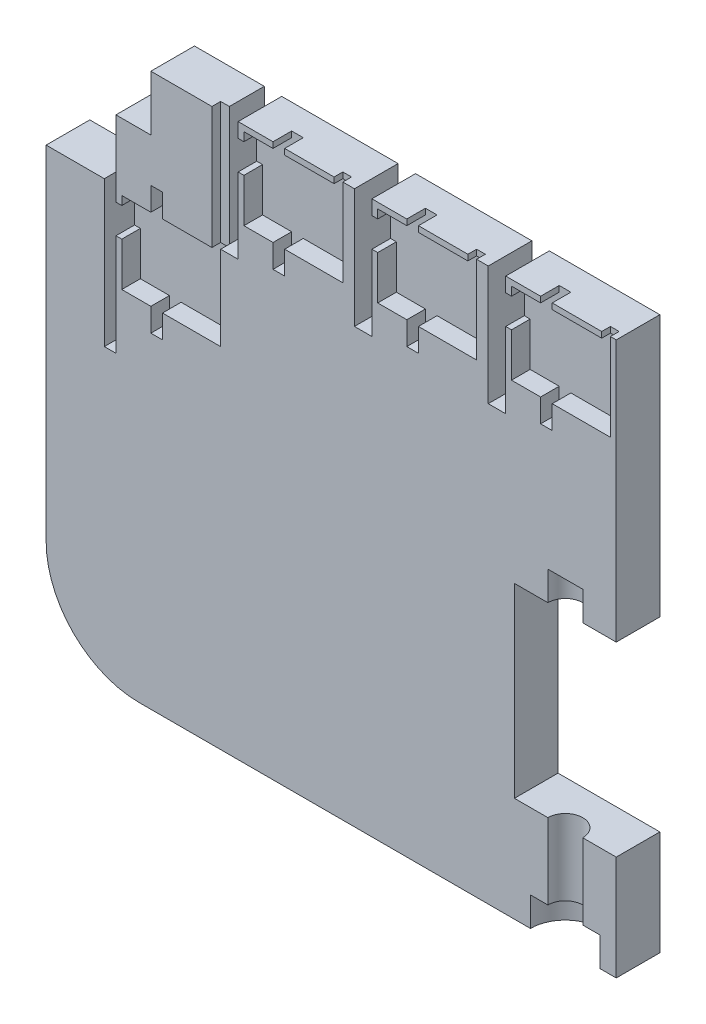
SolidWorks part; units mm, degrees
ref_plane "Front Plane" through (0, 0, 0) normal (0, 0, 1) x (1, 0, 0)
ref_plane "Top Plane" through (0, 0, 0) normal (0, 1, 0) x (1, 0, 0)
ref_plane "Right Plane" through (0, 0, 0) normal (1, 0, 0) x (0, 0, -1)
sketch "Sketch1" plane through (0, 0, 0) normal (0, 0, 1) x (1, 0, 0)
  line L1 (-33, -47.5) -> (49, -47.5)
  line L2 (-49, -31.5) -> (-49, 47.5)
  line L3 (-49, 47.5) -> (27, 47.5)
  line L4 (49, -47.5) -> (49, -29.5)
  line L5 (-49, -47.5) -> (49, 47.5) construction
  line L6 (-49, 47.5) -> (49, -47.5) construction
  line L10 (49, 2.5) -> (31.5, 2.5)
  line L11 (31.5, 2.5) -> (31.5, -29.5)
  line L12 (31.5, -29.5) -> (49, -29.5)
  line L13 (49, 2.5) -> (49, 47.5)
  line L14 (30, 47.5) -> (49, 47.5)
  line L16 (30, 47.5) -> (30, 30.5)
  line L17 (30, 30.5) -> (27, 30.5)
  line L18 (27, 47.5) -> (27, 30.5)
  arc A0 (-33, -47.5) -> (-49, -31.5) centre (-33, -31.5) cw
  point P0 (0, 0)
  point P15 (30, 39)
  dimension "D3" = 16
  dimension "D1" = 98
  dimension "D2" = 95
  dimension "D4" = 18
  dimension "D5" = 17.5
  dimension "D6" = 32
  dimension "D7" = 17
  dimension "D8" = 19
  dimension "D9" = 3
extrude "Boss-Extrude1" add sketch "Sketch1" along normal blind 7.5
sketch "Sketch2" plane through (0, 0, 7.5) normal (0, 0, 1) x (1, 0, 0)
  line L0 (30, 40) -> (31, 40)
  line L1 (30, 47.5) -> (30, 30.5) construction
  line L2 (31, 40) -> (31, 32.5)
  line L3 (31, 32.5) -> (36, 32.5)
  line L4 (36, 32.5) -> (36, 28.5)
  line L5 (36, 28.5) -> (38, 28.5)
  line L6 (38, 28.5) -> (38, 32.5)
  line L7 (38, 32.5) -> (48, 32.5)
  line L8 (48, 32.5) -> (48, 46.5)
  line L9 (48, 46.5) -> (38, 46.5)
  line L10 (31, 46.5) -> (31, 45)
  line L11 (31, 45) -> (30, 45)
  line L12 (30, 45) -> (30, 40)
  line L13 (-16, 40) -> (-15, 40)
  line L14 (36, 46.5) -> (36, 47.5)
  line L15 (49, 47.5) -> (30, 47.5) construction
  line L16 (36, 47.5) -> (38, 47.5)
  line L17 (38, 47.5) -> (38, 46.5)
  line L19 (36, 46.5) -> (31, 46.5)
  line L20 (7, 40) -> (8, 40)
  line L21 (8, 40) -> (8, 32.5)
  line L22 (8, 32.5) -> (13, 32.5)
  line L23 (13, 32.5) -> (13, 28.5)
  line L24 (13, 28.5) -> (15, 28.5)
  line L25 (15, 28.5) -> (15, 32.5)
  line L26 (15, 32.5) -> (25, 32.5)
  line L27 (25, 32.5) -> (25, 46.5)
  line L28 (25, 46.5) -> (15, 46.5)
  line L29 (8, 46.5) -> (8, 45)
  line L30 (8, 45) -> (7, 45)
  line L31 (7, 45) -> (7, 40)
  line L32 (13, 46.5) -> (13, 47.5)
  line L33 (13, 47.5) -> (15, 47.5)
  line L34 (15, 47.5) -> (15, 46.5)
  line L35 (13, 46.5) -> (8, 46.5)
  line L36 (49, 2.5) -> (49, 47.5) construction
  line L37 (27, 47.5) -> (-49, 47.5) construction
  line L38 (-15, 40) -> (-15, 32.5)
  line L39 (-15, 32.5) -> (-10, 32.5)
  line L40 (-10, 32.5) -> (-10, 28.5)
  line L41 (-10, 28.5) -> (-8, 28.5)
  line L42 (-8, 28.5) -> (-8, 32.5)
  line L43 (-8, 32.5) -> (2, 32.5)
  line L44 (2, 32.5) -> (2, 46.5)
  line L45 (2, 46.5) -> (-8, 46.5)
  line L46 (-15, 46.5) -> (-15, 45)
  line L47 (-15, 45) -> (-16, 45)
  line L48 (-16, 45) -> (-16, 40)
  line L49 (-10, 46.5) -> (-10, 47.5)
  line L50 (-10, 47.5) -> (-8, 47.5)
  line L51 (-8, 47.5) -> (-8, 46.5)
  line L52 (-10, 46.5) -> (-15, 46.5)
  point P4 (30, 42.5)
  dimension "D1" = 1
  dimension "D2" = 5
  dimension "D3" = 5
  dimension "D4" = 4
  dimension "D5" = 17
  dimension "D6" = 10
  dimension "D7" = 2
  dimension "D8" = 4
  dimension "D9" = 14
  dimension "D10" = 24
  dimension "D11" = 1
  dimension "D12" = 6
extrude "Cut-Extrude1" cut sketch "Sketch2" against normal blind 3.2
sketch "Sketch3" plane through (0, -47.5, 0) normal (0, -1, 0) x (1, 0, 0)
  line L0 (-33, 7.5) -> (49, 7.5) construction
  line L2 (49, 7.5) -> (31.5, 7.5) construction
  line L4 (34.25, 7.5) -> (46.25, 7.5)
  arc A0 (46.25, 7.5) -> (34.25, 7.5) centre (40.25, 7.5) cw
  point P6 (40.25, 7.5)
  dimension "D2" = 6
  dimension "D1" = 17.5
extrude "Cut-Extrude2" cut sketch "Sketch3" against normal blind 5
sketch "Sketch4" plane through (0, -42.5, 0) normal (0, -1, 0) x (1, 0, 0)
  line L0 (46.25, 7.5) -> (34.25, 7.5) construction
  line L1 (37.25, 7.5) -> (43.25, 7.5)
  arc A0 (43.25, 7.5) -> (37.25, 7.5) centre (40.25, 7.5) cw
  dimension "D1" = 3
extrude "Cut-Extrude3" cut sketch "Sketch4" against normal blind 50
sketch "Sketch5" plane through (0, 0, 7.5) normal (0, 0, 1) x (1, 0, 0)
  line L0 (7, 47.5) -> (7, 30.5)
  line L1 (13, 47.5) -> (-8, 47.5) construction
  line L2 (7, 30.5) -> (4, 30.5)
  line L3 (4, 30.5) -> (4, 47.5)
  line L4 (4, 47.5) -> (7, 47.5)
  line L5 (27, 30.5) -> (27, 47.5) construction
  line L6 (30, 30.5) -> (27, 30.5) construction
  line L7 (7, 45) -> (7, 40) construction
  line L8 (-16, 47.5) -> (-16, 30.5)
  line L9 (-10, 47.5) -> (-49, 47.5) construction
  line L10 (-16, 30.5) -> (-19, 30.5)
  line L11 (-19, 30.5) -> (-19, 47.5)
  line L12 (-19, 47.5) -> (-16, 47.5)
  line L13 (-16, 45) -> (-16, 40) construction
extrude "Cut-Extrude4" cut sketch "Sketch5" against normal up to next
sketch "Sketch8" plane through (0, 0, 7.5) normal (0, 0, 1) x (1, 0, 0)
  line L0 (-19, 47.5) -> (-49, 47.5) construction
  line L1 (-37, 47.5) -> (-49, 47.5)
  line L2 (-37, 47.5) -> (-37, 10.5)
  line L3 (-37, 10.5) -> (-49, 10.5)
  line L4 (-49, 47.5) -> (-49, 10.5)
  line L5 (-49, 47.5) -> (-49, -31.5) construction
  dimension "D1" = 12
  dimension "D2" = 37
extrude "Cut-Extrude5" cut sketch "Sketch8" against normal up to next
sketch "Sketch9" plane through (0, 0, 7.5) normal (0, 0, 1) x (1, 0, 0)
  line L0 (-37, 20) -> (-36, 20)
  line L1 (-36, 20) -> (-36, 12.5)
  line L2 (-36, 12.5) -> (-31, 12.5)
  line L3 (-31, 12.5) -> (-31, 8.5)
  line L4 (-31, 8.5) -> (-29, 8.5)
  line L5 (-29, 8.5) -> (-29, 12.5)
  line L6 (-29, 12.5) -> (-19, 12.5)
  line L7 (-19, 12.5) -> (-19, 26.5)
  line L8 (-19, 26.5) -> (-29, 26.5)
  line L9 (-36, 26.5) -> (-36, 25)
  line L10 (-36, 25) -> (-37, 25)
  line L11 (-37, 25) -> (-37, 20)
  line L12 (-31, 26.5) -> (-31, 30.5)
  line L13 (-31, 30.5) -> (-29, 30.5)
  line L14 (-29, 30.5) -> (-29, 26.5)
  line L15 (-31, 26.5) -> (-36, 26.5)
  line L16 (-49, 10.5) -> (-37, 10.5) construction
  line L17 (-37, 10.5) -> (-37, 47.5) construction
  point P2 (-37, 22.5)
  dimension "D1" = 14
  dimension "D2" = 17
  dimension "D3" = 10
  dimension "D4" = 2
  dimension "D5" = 5
  dimension "D6" = 4
  dimension "D7" = 7.5
  dimension "D8" = 5
  dimension "D9" = 1
  dimension "D10" = 4
  dimension "D11" = 12
extrude "Cut-Extrude6" cut sketch "Sketch9" against normal blind 3.2
sketch "Sketch10" plane through (0, 10.5, 0) normal (0, 1, 0) x (1, 0, 0)
  line L0 (-49, -7.5) -> (-37, -7.5) construction
  line L1 (-49, 0) -> (-39, 0)
  line L2 (-49, 0) -> (-49, -7.5)
  line L3 (-49, -7.5) -> (-39, -7.5)
  line L4 (-39, 0) -> (-39, -7.5)
  dimension "D1" = 10
extrude "Boss-Extrude2" add sketch "Sketch10" along normal blind 17
sketch "Sketch11" plane through (0, 30.5, 0) normal (0, 1, 0) x (1, 0, 0)
  line L1 (-19, 0) -> (-16, 0)
  line L2 (-19, 0) -> (-19, -7.5)
  line L3 (-19, -7.5) -> (-16, -7.5)
  line L4 (-16, 0) -> (-16, -7.5)
  line L5 (4, 0) -> (7, 0)
  line L6 (4, 0) -> (4, -7.5)
  line L7 (4, -7.5) -> (7, -7.5)
  line L8 (7, 0) -> (7, -7.5)
  line L9 (27, 0) -> (30, 0)
  line L10 (27, 0) -> (27, -7.5)
  line L11 (27, -7.5) -> (30, -7.5)
  line L12 (30, 0) -> (30, -7.5)
extrude "Cut-Extrude7" cut sketch "Sketch11" against normal blind 3.5
sketch "Sketch12" plane through (0, 10.5, 0) normal (0, 1, 0) x (1, 0, 0)
  line L1 (-37, 0) -> (-39, 0)
  line L2 (-37, 0) -> (-37, -7.5)
  line L3 (-37, -7.5) -> (-39, -7.5)
  line L4 (-39, 0) -> (-39, -7.5)
extrude "Cut-Extrude8" cut sketch "Sketch12" against normal blind 4
sketch "Sketch13" plane through (0, 6.5, 0) normal (0, 1, 0) x (1, 0, 0)
  line L1 (-39, 0) -> (-37, 0)
  line L2 (-39, 0) -> (-39, -7.5)
  line L3 (-39, -7.5) -> (-37, -7.5)
  line L4 (-37, 0) -> (-37, -7.5)
extrude "Cut-Extrude9" cut sketch "Sketch13" against normal blind 4
sketch "Sketch14" plane through (-37, 0, 0) normal (-1, 0, 0) x (0, 0, 1)
  line L0 (7.5, 25) -> (7.5, 47.5) construction
  line L1 (0, 47.5) -> (7.5, 47.5)
  line L2 (0, 47.5) -> (0, 38)
  line L3 (0, 38) -> (7.5, 38)
  line L4 (7.5, 47.5) -> (7.5, 38)
  dimension "D1" = 13
extrude "Cut-Extrude10" cut sketch "Sketch14" against normal blind 6
sketch "Sketch15" plane through (0, 0, 7.5) normal (0, 0, 1) x (1, 0, 0)
  line L0 (-19, 26.5) -> (-29, 26.5) construction
  line L1 (-19, 47.5) -> (-20.5, 47.5)
  line L2 (-19, 47.5) -> (-19, 26.5)
  line L3 (-19, 26.5) -> (-20.5, 26.5)
  line L4 (-20.5, 47.5) -> (-20.5, 26.5)
  line L5 (4, 47.5) -> (-8, 47.5) construction
  line L6 (2, 46.5) -> (0.5, 46.5)
  line L7 (2, 46.5) -> (2, 47.5)
  line L8 (2, 47.5) -> (0.5, 47.5)
  line L9 (0.5, 46.5) -> (0.5, 47.5)
  line L10 (27, 47.5) -> (15, 47.5) construction
  line L11 (25, 46.5) -> (23.5, 46.5)
  line L12 (25, 46.5) -> (25, 47.5)
  line L13 (25, 47.5) -> (23.5, 47.5)
  line L14 (23.5, 46.5) -> (23.5, 47.5)
  line L15 (49, 47.5) -> (38, 47.5) construction
  line L16 (48, 46.5) -> (46.5, 46.5)
  line L17 (48, 46.5) -> (48, 47.5)
  line L18 (48, 47.5) -> (46.5, 47.5)
  line L19 (46.5, 46.5) -> (46.5, 47.5)
  dimension "D1" = 1.5
  dimension "D2" = 1.5
  dimension "D3" = 1.5
  dimension "D4" = 1.5
extrude "Cut-Extrude11" cut sketch "Sketch15" against normal blind 1.5
ref_plane "Plane1" through (0, 0, 17.5) normal (0, 0, 1) x (1, 0, 0)
